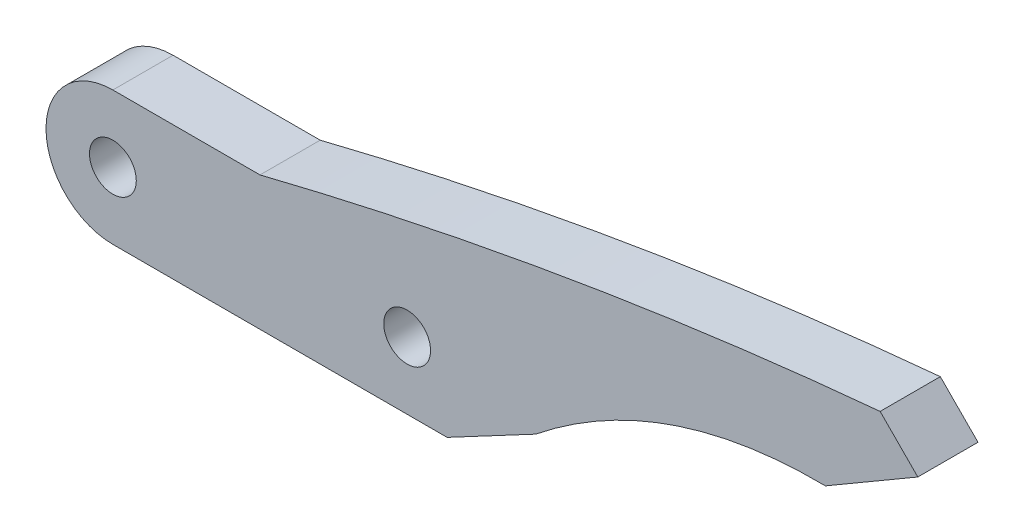
SolidWorks part; units mm, degrees
ref_plane "Front Plane" through (0, 0, 0) normal (0, 0, 1) x (1, 0, 0)
ref_plane "Top Plane" through (0, 0, 0) normal (0, 1, 0) x (1, 0, 0)
ref_plane "Right Plane" through (0, 0, 0) normal (1, 0, 0) x (0, 0, -1)
sketch "Sketch2" plane through (0, 0, 0) normal (0, 0, 1) x (1, 0, 0)
  line L0 (-11, 0) -> (11, 0) construction
  line L1 (0, 0) -> (0, 3.7726) construction
  line L3 (11, -5) -> (-11, -5)
  line L5 (11, 5) -> (-11, 5)
  line L7 (13.6225, -4.257) -> (-13.6225, 4.257) construction
  line L8 (13.6225, 4.257) -> (-13.6225, -4.257) construction
  circle A0 centre (-11, 0) radius 1.75
  circle A1 centre (-11, 0) radius 5
  circle A2 centre (11, 0) radius 5
  circle A3 centre (11, 0) radius 1.75
  point P4 (0, 0)
  dimension "D2" = 3.5
  dimension "D3" = 10
  dimension "D1" = 22
  dimension "D4" = 22
extrude "Boss-Extrude3" add sketch "Sketch2" along normal blind 4.5 contours L3 A2 L5 A1 | A1 A0 | A2 A3
sketch "Sketch3" plane through (0, 0, 4.5) normal (0, 0, 1) x (1, 0, 0)
  line L0 (49.1808, 10.03) -> (42.27, 6)
  line L1 (49.1808, 10.03) -> (46.364, 12.87)
  line L2 (11, -5) -> (-11, -5) construction
  line L3 (11, 0) -> (11, -5) construction
  line L4 (20.61, -1.48) -> (13.99, -5)
  line L5 (11, -5) -> (13.99, -5)
  line L6 (11, 5) -> (-11, 5) construction
  line L8 (11, 5) -> (0, 5)
  arc A0 (11, -5) -> (11, 5) centre (11, 0) ccw construction
  arc A2 (11, -5) -> (11, 5) centre (11, 0) ccw
  spline S0 degree 2 poles (42.27, 6) (30.1462, 6.1573) (20.61, -1.48) knots 0 0 0 1 1 1
  spline S1 degree 2 poles (0, 5) (22.8855, 10.7079) (46.364, 12.87) knots 0 0 0 1 1 1
  dimension "D1" = 4
  dimension "D2" = 8
  dimension "D3" = 17.87
  dimension "D4" = 15.03
  dimension "D5" = 11
  dimension "D6" = 9.45
  dimension "D7" = 3.52
  dimension "D8" = 9.61
  dimension "D9" = 20.52
  dimension "D10" = 31.27
  dimension "D11" = 2.99
  dimension "D12" = 13.52
  dimension "D13" = 15.07
extrude "Boss-Extrude4" add sketch "Sketch3" against normal up to surface (4.5 mm away) up to face at (0, 0, 0)
